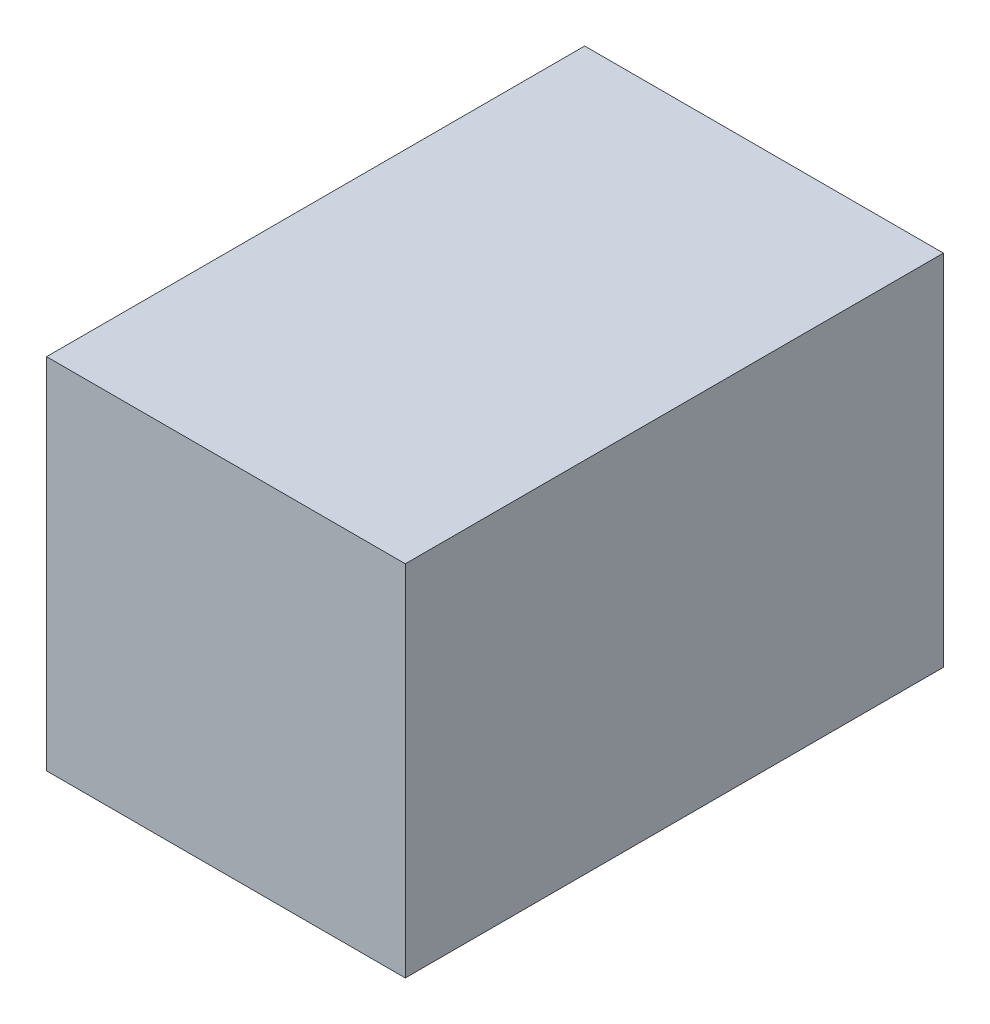
SolidWorks part; units mm, degrees
material "1.0038 (S235JRG2)"
ref_plane "Ebene vorne" through (0, 0, 0) normal (0, 0, 1) x (1, 0, 0)
ref_plane "Ebene oben" through (0, 0, 0) normal (0, 1, 0) x (1, 0, 0)
ref_plane "Ebene rechts" through (0, 0, 0) normal (1, 0, 0) x (0, 0, -1)
sketch "Skizze1" plane through (0, 0, 0) normal (0, 0, 1) x (1, 0, 0)
  line L1 (-10, -10) -> (10, -10)
  line L2 (-10, -10) -> (-10, 10)
  line L3 (-10, 10) -> (10, 10)
  line L4 (10, -10) -> (10, 10)
  dimension "D1" = 20
  dimension "D2" = 20
  dimension "D3" = 10
  dimension "D4" = 10
extrude "Aufsatz-Linear austragen1" add sketch "Skizze1" along normal blind 30
